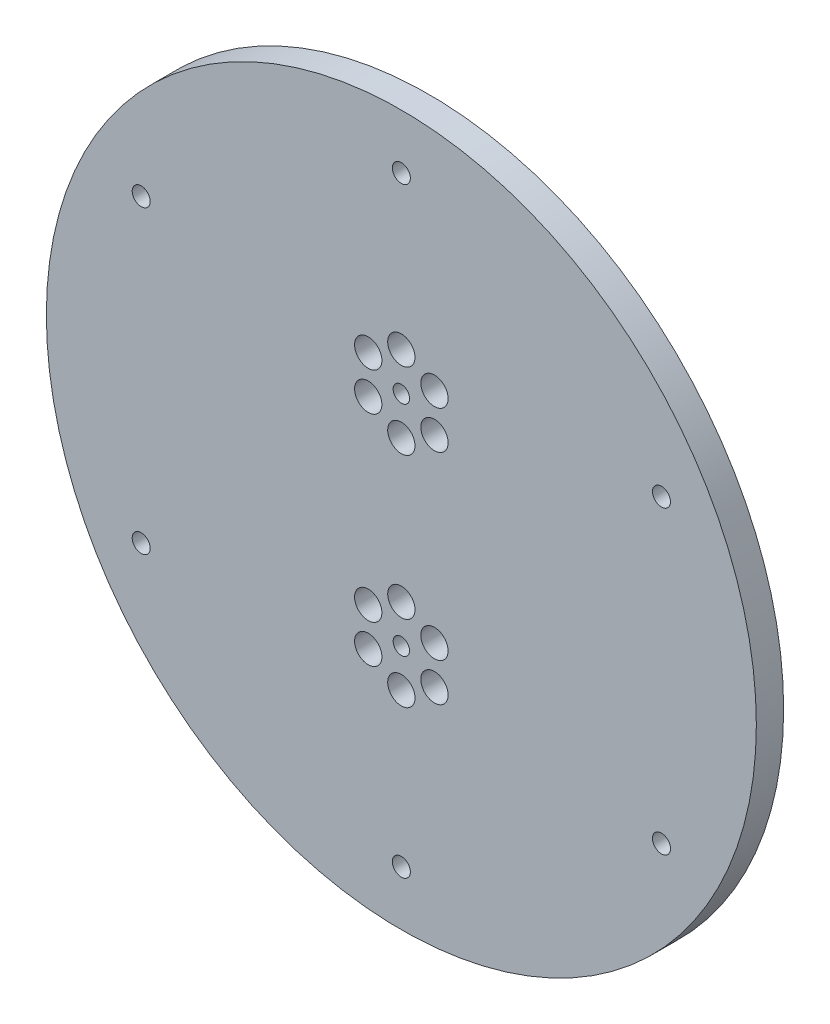
SolidWorks part; units mm, degrees
ref_plane "Front Plane" through (0, 0, 0) normal (0, 0, 1) x (1, 0, 0)
ref_plane "Top Plane" through (0, 0, 0) normal (0, 1, 0) x (1, 0, 0)
ref_plane "Right Plane" through (0, 0, 0) normal (1, 0, 0) x (0, 0, -1)
sketch "Sketch1" plane through (0, 0, 0) normal (0, 0, 1) x (1, 0, 0)
  line L0 (0, 65) -> (0, -65) construction
  line L1 (0, 0) -> (65, 0) construction
  circle A0 centre (0, 0) radius 65
  circle A2 centre (0, 0) radius 55 construction
  circle A3 centre (0, 55) radius 1.65
  circle A4 centre (47.6314, 27.5) radius 1.65
  circle A5 centre (47.6314, -27.5) radius 1.65
  circle A6 centre (0, -55) radius 1.65
  circle A7 centre (-47.6314, -27.5) radius 1.65
  circle A8 centre (-47.6314, 27.5) radius 1.65
  circle A9 centre (0, 0) radius 7 construction
  circle A10 centre (0, 0) radius 1.5 construction
  circle A11 centre (0, 7) radius 2.5 construction
  circle A12 centre (6.0622, 3.5) radius 2.5 construction
  circle A13 centre (6.0622, -3.5) radius 2.5 construction
  circle A14 centre (0, -7) radius 2.5 construction
  circle A15 centre (-6.0622, -3.5) radius 2.5 construction
  circle A16 centre (-6.0622, 3.5) radius 2.5 construction
  circle A17 centre (0, 20) radius 7 construction
  circle A18 centre (0, 27) radius 2.5
  circle A19 centre (6.0622, 23.5) radius 2.5
  circle A20 centre (6.0622, 16.5) radius 2.5
  circle A21 centre (0, 13) radius 2.5
  circle A22 centre (-6.0622, 16.5) radius 2.5
  circle A23 centre (-6.0622, 23.5) radius 2.5
  circle A24 centre (0, 20) radius 1.5
  circle A25 centre (6.0622, -16.5) radius 2.5
  circle A26 centre (0, -13) radius 2.5
  circle A27 centre (-6.0622, -16.5) radius 2.5
  circle A28 centre (0, -20) radius 1.5
  circle A29 centre (-6.0622, -23.5) radius 2.5
  circle A30 centre (0, -27) radius 2.5
  circle A31 centre (6.0622, -23.5) radius 2.5
  point P19 (0, 0)
  point P33 (0, 0)
  point P51 (0, 20)
  dimension "D1" = 130
  dimension "D2" = 14
  dimension "D3" = 10
  dimension "D4" = 3.3
  dimension "D6" = 6
  dimension "D7" = 5
  dimension "D8" = 3
  dimension "D9" = 14
  dimension "D10" = 20
  dimension "D5" = 6
  dimension "D11" = 6
extrude "Boss-Extrude1" add sketch "Sketch1" along normal blind 5
